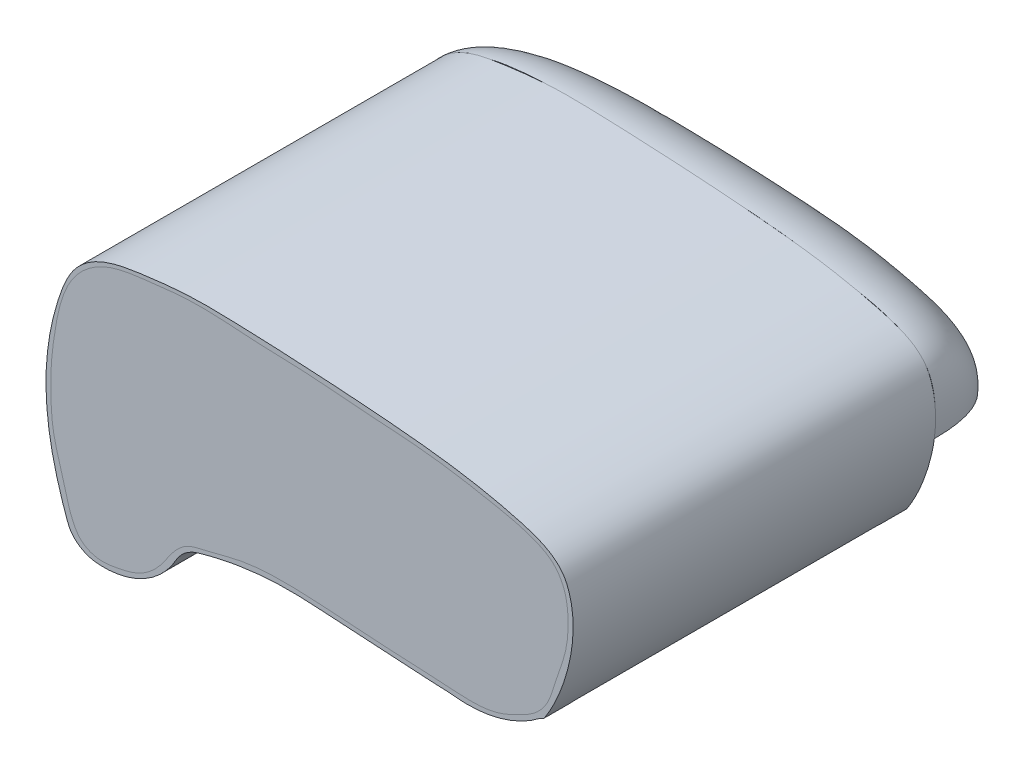
SolidWorks part; units mm, degrees
ref_plane "Front Plane" through (0, 0, 0) normal (0, 0, 1) x (1, 0, 0)
ref_plane "Top Plane" through (0, 0, 0) normal (0, 1, 0) x (1, 0, 0)
ref_plane "Right Plane" through (0, 0, 0) normal (1, 0, 0) x (0, 0, -1)
sketch "Sketch3" plane through (0, 0, 0) normal (0, 0, 1) x (1, 0, 0)
  spline S3 degree 3 poles (-30.4158, -23.6816) (-26.3483, -23.8865) (-22.7046, -22.0674) (-20.4239, -18.6933) (-20.304, -18.5158) (-20.0741, -18.1541) (-19.7633, -17.5878) (-19.5076, -17.2429) (-19.3692, -17.0794) (-18.9513, -16.5856) (-18.4465, -16.181) (-17.8735, -15.8807) (-17.7803, -15.8319) (-17.591, -15.7401) (-17.2995, -15.6137) (-17.0982, -15.5528) (-16.9975, -15.5227) (-16.8928, -15.4914) (-16.6834, -15.4297) (-16.3685, -15.3393) (-16.1582, -15.2807) (-16.0529, -15.2517) (-12.5144, -14.2781) (-8.9004, -13.7487) (-5.2109, -13.6634) (-4.334, -13.6431) (-2.579, -13.6529) (0.0505, -13.8184) (1.8017, -13.9228) (2.6773, -13.9751) (6.5229, -14.2044) (10.3686, -14.4338) (14.2143, -14.6631) (14.784, -14.6971) (15.9235, -14.7651) (17.6362, -14.8094) (18.7722, -14.935) (19.342, -14.9689) (20.3187, -15.0272) (21.2863, -14.9999) (22.7246, -14.8352) (23.2019, -14.7596) (24.152, -14.5659) (24.6269, -14.4472) (26.0289, -14.0294) (26.9249, -13.6727) (28.6409, -12.8057) (29.461, -12.2955) (30.2398, -11.7019) (30.3143, -11.6452) (30.4622, -11.5303) (30.7884, -11.4725) (30.8923, -11.3167) (30.9437, -11.2384) (31.0764, -11.0361) (31.4317, -10.4693) (31.9497, -9.5397) (32.4855, -8.4558) (32.9579, -7.3766) (33.3755, -6.2991) (33.7422, -5.2207) (34.0616, -4.1386) (34.4235, -2.6865) (34.6881, -1.2133) (34.8374, 0.2928) (34.8822, 1.442) (34.8472, 2.6121) (34.7158, 3.8044) (34.4597, 5.0136) (34.1873, 5.8271) (33.9324, 6.4006) (33.7637, 6.7398) (33.4613, 7.2204) (33.1649, 7.5894) (32.9057, 7.8653) (32.7012, 8.0623) (32.488, 8.2493) (32.2666, 8.4267) (32.0381, 8.5948) (31.8032, 8.7539) (31.5628, 8.9044) (31.2356, 9.0943) (30.8158, 9.3126) (30.2997, 9.5483) (29.7737, 9.7616) (29.2405, 9.9561) (28.5222, 10.1946) (27.6144, 10.4609) (26.5177, 10.7556) (25.416, 11.0318) (24.3094, 11.2896) (23.1984, 11.5293) (22.0832, 11.7516) (20.9645, 11.9577) (19.8424, 12.1484) (18.7174, 12.3245) (17.5896, 12.4872) (16.4595, 12.6376) (15.3272, 12.7768) (14.1929, 12.9061) (13.0567, 13.0265) (12.1085, 13.1204) (11.3492, 13.1922) (10.5893, 13.2619) (9.8286, 13.329) (9.1624, 13.3856) (8.7816, 13.4174) (8.4006, 13.4489) (7.9241, 13.4876) (7.1613, 13.5482) (6.3978, 13.6069) (5.6334, 13.6638) (5.169, 13.6977) (4.8955, 13.7173) (4.8134, 13.7232) (4.2136, 13.7661) (3.0136, 13.849) (1.2132, 13.9656) (0.0127, 14.0384) (-0.5877, 14.0736) (-0.6245, 14.0757) (-0.7575, 14.0835) (-0.9869, 14.0968) (-1.3724, 14.119) (-1.8545, 14.1462) (-2.4334, 14.1782) (-3.0128, 14.2094) (-3.5926, 14.24) (-4.1729, 14.2698) (-4.7537, 14.2989) (-5.5287, 14.3368) (-6.4986, 14.3823) (-7.6646, 14.4337) (-8.8326, 14.482) (-10.0027, 14.5267) (-11.175, 14.5674) (-12.3496, 14.6034) (-13.5265, 14.634) (-14.7059, 14.6542) (-15.8878, 14.6587) (-17.0719, 14.6418) (-18.2579, 14.5973) (-19.445, 14.5251) (-20.6326, 14.4248) (-21.8208, 14.3024) (-23.01, 14.1637) (-24.2001, 14.0094) (-25.3912, 13.8403) (-26.5814, 13.6466) (-27.7691, 13.4185) (-28.942, 13.1088) (-30.0893, 12.7041) (-31.0083, 12.2678) (-31.71, 11.8539) (-32.3847, 11.3953) (-33.1682, 10.7362) (-33.8525, 9.97) (-34.3289, 9.3004) (-34.7606, 8.5994) (-35.2215, 7.6762) (-35.534, 6.91) (-35.6795, 6.5221) (-35.9046, 5.9225) (-36.2112, 4.9903) (-36.5846, 3.6945) (-36.8438, 2.6961) (-37.0792, 1.6712) (-37.2881, 0.6207) (-37.4681, -0.4544) (-37.6656, -1.9187) (-37.8261, -3.8027) (-37.8684, -6.1288) (-37.7497, -8.4955) (-37.4776, -10.8739) (-37.0598, -13.2353) (-36.5177, -15.556) (-35.9805, -17.4362) (-35.511, -18.9018) (-35.2251, -19.7368) (-35.0582, -20.2058) (-35.0172, -20.3198) (-34.8031, -20.9157) (-34.3569, -22.1011) (-32.3076, -23.4804) (-31.0481, -23.6498) (-30.4158, -23.6816) (-26.3483, -23.8865) (-22.7046, -22.0674) knots -0.008045 0 0 0 0.061141 0.061141 0.061141 0.06466 0.068178 0.071696 0.071696 0.071696 0.082191 0.082191 0.082191 0.083918 0.085645 0.087372 0.087372 0.087372 0.089165 0.090958 0.092751 0.092751 0.092751 0.153029 0.153029 0.153029 0.167356 0.181683 0.19601 0.19601 0.19601 0.258935 0.258935 0.258935 0.268257 0.27758 0.286902 0.286902 0.286902 0.302883 0.302883 0.310873 0.310873 0.318863 0.318863 0.334844 0.334844 0.350825 0.350825 0.350825 0.352353 0.353881 0.35541 0.35541 0.35541 0.359359 0.366469 0.37358 0.380691 0.387801 0.394912 0.402023 0.409133 0.423355 0.430465 0.437576 0.444687 0.451797 0.458908 0.466019 0.466019 0.469086 0.472153 0.47522 0.476754 0.478288 0.479821 0.481355 0.482889 0.484422 0.485956 0.48749 0.490557 0.493624 0.496691 0.499759 0.502826 0.508961 0.515095 0.52123 0.527364 0.533499 0.539633 0.545768 0.551902 0.558037 0.564172 0.570306 0.576441 0.582575 0.58871 0.594844 0.597912 0.600979 0.607114 0.610181 0.611715 0.613248 0.616315 0.619383 0.625517 0.628585 0.631652 0.632969 0.632969 0.632969 0.642586 0.652203 0.66182 0.66182 0.66182 0.662408 0.663951 0.665493 0.668578 0.671663 0.674748 0.677833 0.680918 0.684003 0.687088 0.693258 0.699428 0.705598 0.711768 0.717938 0.724108 0.730278 0.736448 0.742618 0.748788 0.754958 0.761128 0.767298 0.773468 0.779638 0.785808 0.791978 0.798148 0.804318 0.810488 0.816658 0.822828 0.825913 0.828998 0.835168 0.841338 0.844423 0.847508 0.853678 0.859848 0.859848 0.859848 0.869388 0.874158 0.878928 0.883697 0.888467 0.893237 0.898007 0.907547 0.917087 0.926626 0.936166 0.945706 0.955246 0.964785 0.969555 0.974325 0.975865 0.975865 0.975865 0.98391 0.991955 1 1 1 1.061141 1.061141 1.061141 weights 1 0.914065 0.914065 1 1 1 1 1 1 0.987638 0.987638 1 1 1 1 1 1 1 1 1 1 1 1 1 1 1 1 1 1 1 1 1 1 1 1 1 1 1 1 1 1 1 1 1 1 1 1 1 1 1 1 1 1 1 1 1 1 1 1 1 1 1 1 1 1 1 1 1 1 1 1 1 1 1 1 1 1 1 1 1 1 1 1 1 1 1 1 1 1 1 1 1 1 1 1 1 1 1 1 1 1 1 1 1 1 1 1 1 1 1 1 1 1 1 1 1 1 1 1 1 1 1 1 1 1 1 1 1 1 1 1 1 1 1 1 1 1 1 1 1 1 1 1 1 1 1 1 1 1 1 1 1 1 1 1 1 1 1 1 1 1 1 1 1 1 1 1 1 1 1 1 1 1 1 1 1 1 1 1 1 1 1 1 1 1 1 0.914065 0.914065 only from (-30.4158, -23.6816) to (-30.4158, -23.6816)
extrude "Boss-Extrude2" add sketch "Sketch3" along normal blind 50 contours S3
sketch "Sketch9" plane through (0, 0, 0) normal (0, 0, -1) x (-1, 0, 0)
  spline S0 degree 3 poles (-33.7977, 5.4801) (-34.2769, 2.2354) (-34.1307, -1.2126) (-33.109, -4.2704) (-32.2134, -6.809) (-31.5466, -9.246) (-29.7466, -11.4487) (-27.1947, -12.8028) (-24.1608, -14.2194) (-20.3031, -14.453) (-16.4026, -14.0795) (-12.0077, -13.963) (-7.3255, -13.6383) (-2.5563, -13.3667) (1.662, -13.0676) (6.216, -12.9574) (10.8881, -13.2764) (15.1467, -14.5868) (18.3871, -15.1317) (20.5451, -17.2018) (22.0719, -19.8862) (24.7577, -22.1348) (27.9522, -22.8781) (30.6512, -23.2861) (33.324, -22.1675) (34.7011, -19.1807) (35.5824, -15.3471) (36.9492, -11.2903) (37.1798, -7.2911) (37.2241, -3.3615) (36.5434, 2.162) (35.2376, 8.5059) (29.7403, 12.8242) (23.7734, 13.5518) (16.5418, 14.4104) (9.2281, 13.6486) (1.7371, 13.5774) (-5.373, 12.8392) (-12.6921, 12.5283) (-19.0263, 11.6976) (-24.4576, 10.6457) (-28.6935, 9.775) (-32.2385, 8.0599) (-33.7977, 5.4801) (-34.2769, 2.2354) (-34.1307, -1.2126) knots -0.045991 -0.028791 -0.014028 0 0.0233 0.040373 0.051295 0.066461 0.080359 0.09526 0.112321 0.133474 0.155863 0.175167 0.203706 0.230933 0.251572 0.2713 0.30388 0.325554 0.343002 0.354716 0.371808 0.392562 0.408082 0.423887 0.435416 0.451508 0.473479 0.499302 0.519191 0.537282 0.561981 0.608952 0.634675 0.667939 0.703139 0.751398 0.784732 0.822979 0.865597 0.901841 0.925029 0.954009 0.971209 0.985972 1 1.0233 1.040373 1.051295 only from (-34.1289, 2.8072) to (-34.1289, 2.8072)
extrude "Cut-Extrude4" cut sketch "Sketch9" against normal blind 50
sketch "Sketch17" plane through (0, 0, 0) normal (0, 0, -1) x (-1, 0, 0)
  line L0 (-34.6868, -1.0559) -> (35.6264, 6.6621)
  spline S0 degree 3 poles (30.4158, -23.6816) (31.0481, -23.6498) (32.3076, -23.4804) (34.3569, -22.1011) (34.8031, -20.9157) (35.0172, -20.3198) (35.0582, -20.2058) (35.2251, -19.7368) (35.511, -18.9018) (35.9805, -17.4362) (36.5177, -15.556) (37.0598, -13.2353) (37.4776, -10.8739) (37.7497, -8.4955) (37.8684, -6.1288) (37.8261, -3.8027) (37.6656, -1.9187) (37.4681, -0.4544) (37.2881, 0.6207) (37.0792, 1.6712) (36.8438, 2.6961) (36.5846, 3.6945) (36.2112, 4.9903) (35.9046, 5.9225) (35.6795, 6.5221) (35.534, 6.91) (35.2215, 7.6762) (34.7606, 8.5994) (34.3289, 9.3004) (33.8525, 9.97) (33.1682, 10.7362) (32.3847, 11.3953) (31.71, 11.8539) (31.0083, 12.2678) (30.0893, 12.7041) (28.942, 13.1088) (27.7691, 13.4185) (26.5814, 13.6466) (25.3912, 13.8403) (24.2001, 14.0094) (23.01, 14.1637) (21.8208, 14.3024) (20.6326, 14.4248) (19.445, 14.5251) (18.2579, 14.5973) (17.0719, 14.6418) (15.8878, 14.6587) (14.7059, 14.6542) (13.5265, 14.634) (12.3496, 14.6034) (11.175, 14.5674) (10.0027, 14.5267) (8.8326, 14.482) (7.6646, 14.4337) (6.4986, 14.3823) (5.5287, 14.3368) (4.7537, 14.2989) (4.1729, 14.2698) (3.5926, 14.24) (3.0128, 14.2094) (2.4334, 14.1782) (1.8545, 14.1462) (1.3724, 14.119) (0.9869, 14.0968) (0.7575, 14.0835) (0.6245, 14.0757) (0.5877, 14.0736) (-0.0127, 14.0384) (-1.2132, 13.9656) (-3.0136, 13.849) (-4.2136, 13.7661) (-4.8134, 13.7232) (-4.8955, 13.7173) (-5.169, 13.6977) (-5.6334, 13.6638) (-6.3978, 13.6069) (-7.1613, 13.5482) (-7.9241, 13.4876) (-8.4006, 13.4489) (-8.7816, 13.4174) (-9.1624, 13.3856) (-9.8286, 13.329) (-10.5893, 13.2619) (-11.3492, 13.1922) (-12.1085, 13.1204) (-13.0567, 13.0265) (-14.1929, 12.9061) (-15.3272, 12.7768) (-16.4595, 12.6376) (-17.5896, 12.4872) (-18.7174, 12.3245) (-19.8424, 12.1484) (-20.9645, 11.9577) (-22.0832, 11.7516) (-23.1984, 11.5293) (-24.3094, 11.2896) (-25.416, 11.0318) (-26.5177, 10.7556) (-27.6144, 10.4609) (-28.5222, 10.1946) (-29.2405, 9.9561) (-29.7737, 9.7616) (-30.2997, 9.5483) (-30.8158, 9.3126) (-31.2356, 9.0943) (-31.5628, 8.9044) (-31.8032, 8.7539) (-32.0381, 8.5948) (-32.2666, 8.4267) (-32.488, 8.2493) (-32.7012, 8.0623) (-32.9057, 7.8653) (-33.1649, 7.5894) (-33.4613, 7.2204) (-33.7637, 6.7398) (-33.9324, 6.4006) (-34.1873, 5.8271) (-34.4597, 5.0136) (-34.7158, 3.8044) (-34.8472, 2.6121) (-34.8822, 1.442) (-34.8374, 0.2928) (-34.6881, -1.2133) (-34.4235, -2.6865) (-34.0616, -4.1386) (-33.7422, -5.2207) (-33.3755, -6.2991) (-32.9579, -7.3766) (-32.4855, -8.4558) (-31.9497, -9.5397) (-31.4317, -10.4693) (-31.0764, -11.0361) (-30.9437, -11.2384) (-30.8923, -11.3167) (-30.7884, -11.4725) (-30.4622, -11.5303) (-30.3143, -11.6452) (-30.2398, -11.7019) (-29.461, -12.2955) (-28.6409, -12.8057) (-26.9249, -13.6727) (-26.0289, -14.0294) (-24.6269, -14.4472) (-24.152, -14.5659) (-23.2019, -14.7596) (-22.7246, -14.8352) (-21.2863, -14.9999) (-20.3187, -15.0272) (-19.342, -14.9689) (-18.7722, -14.935) (-17.6362, -14.8094) (-15.9235, -14.7651) (-14.784, -14.6971) (-14.2143, -14.6631) (-10.3686, -14.4338) (-6.5229, -14.2044) (-2.6773, -13.9751) (-1.8017, -13.9228) (-0.0505, -13.8184) (2.579, -13.6529) (4.334, -13.6431) (5.2109, -13.6634) (8.9004, -13.7487) (12.5144, -14.2781) (16.0529, -15.2517) (16.1582, -15.2807) (16.3685, -15.3393) (16.6834, -15.4297) (16.8928, -15.4914) (16.9975, -15.5227) (17.0982, -15.5528) (17.2995, -15.6137) (17.591, -15.7401) (17.7803, -15.8319) (17.8735, -15.8807) (18.4465, -16.181) (18.9513, -16.5856) (19.3692, -17.0794) (19.5076, -17.2429) (19.7633, -17.5878) (20.0741, -18.1541) (20.304, -18.5158) (20.4239, -18.6933) (22.7046, -22.0674) (26.3483, -23.8865) (30.4158, -23.6816) (31.0481, -23.6498) (32.3076, -23.4804) knots -0.061141 0 0 0 0.008045 0.01609 0.024135 0.024135 0.024135 0.025675 0.030445 0.035215 0.044754 0.054294 0.063834 0.073374 0.082913 0.092453 0.101993 0.106763 0.111533 0.116303 0.121072 0.125842 0.130612 0.140152 0.140152 0.140152 0.146322 0.152492 0.155577 0.158662 0.164832 0.171002 0.174087 0.177172 0.183342 0.189512 0.195682 0.201852 0.208022 0.214192 0.220362 0.226532 0.232702 0.238872 0.245042 0.251212 0.257382 0.263552 0.269722 0.275892 0.282062 0.288232 0.294402 0.300572 0.306742 0.312912 0.315997 0.319082 0.322167 0.325252 0.328337 0.331422 0.334507 0.336049 0.337592 0.33818 0.33818 0.33818 0.347797 0.357414 0.367031 0.367031 0.367031 0.368348 0.371415 0.374483 0.380617 0.383685 0.386752 0.388285 0.389819 0.392886 0.399021 0.402088 0.405156 0.41129 0.417425 0.423559 0.429694 0.435828 0.441963 0.448098 0.454232 0.460367 0.466501 0.472636 0.47877 0.484905 0.491039 0.497174 0.500241 0.503309 0.506376 0.509443 0.51251 0.514044 0.515578 0.517111 0.518645 0.520179 0.521712 0.523246 0.52478 0.527847 0.530914 0.533981 0.533981 0.541092 0.548203 0.555313 0.562424 0.569535 0.576645 0.590867 0.597977 0.605088 0.612199 0.619309 0.62642 0.633531 0.640641 0.64459 0.64459 0.64459 0.646119 0.647647 0.649175 0.649175 0.649175 0.665156 0.665156 0.681137 0.681137 0.689127 0.689127 0.697117 0.697117 0.713098 0.713098 0.713098 0.72242 0.731743 0.741065 0.741065 0.741065 0.80399 0.80399 0.80399 0.818317 0.832644 0.846971 0.846971 0.846971 0.907249 0.907249 0.907249 0.909042 0.910835 0.912628 0.912628 0.912628 0.914355 0.916082 0.917809 0.917809 0.917809 0.928304 0.928304 0.928304 0.931822 0.93534 0.938859 0.938859 0.938859 1 1 1 1.008045 1.01609 1.024135 weights 1 1 1 1 1 1 1 1 1 1 1 1 1 1 1 1 1 1 1 1 1 1 1 1 1 1 1 1 1 1 1 1 1 1 1 1 1 1 1 1 1 1 1 1 1 1 1 1 1 1 1 1 1 1 1 1 1 1 1 1 1 1 1 1 1 1 1 1 1 1 1 1 1 1 1 1 1 1 1 1 1 1 1 1 1 1 1 1 1 1 1 1 1 1 1 1 1 1 1 1 1 1 1 1 1 1 1 1 1 1 1 1 1 1 1 1 1 1 1 1 1 1 1 1 1 1 1 1 1 1 1 1 1 1 1 1 1 1 1 1 1 1 1 1 1 1 1 1 1 1 1 1 1 1 1 1 1 1 1 1 1 1 1 1 1 1 1 1 1 1 1 1 1 1 1 0.987638 0.987638 1 1 1 1 1 1 0.914065 0.914065 1 1 1 only from (30.4158, -23.6816) to (30.4158, -23.6816) construction
  spline S1 degree 3 poles (-34.6868, -1.0559) (-34.9459, 1.4826) (-35.1783, 6.9566) (-29.3346, 10.198) (-23.6766, 11.4658) (-16.1466, 12.8119) (-7.7529, 13.5278) (0.621, 14.0984) (9.4185, 14.5408) (18.0794, 14.7646) (28.0773, 13.8367) (34.5801, 10.9823) (35.6264, 6.6621) knots 0 0 0 0 0.105545 0.158729 0.2294 0.320597 0.438441 0.53874 0.628645 0.762133 0.855322 1 1 1 1
revolve "Revolve1" add sketch "Sketch17" angle 90 about L0
sketch "Sketch18" plane through (0, 0, 0) normal (0, 0, 1) x (1, 0, 0)
  spline S3 degree 3 poles (-30.4158, -23.6816) (-26.3483, -23.8865) (-22.7046, -22.0674) (-20.4239, -18.6933) (-20.304, -18.5158) (-20.0741, -18.1541) (-19.7633, -17.5878) (-19.5076, -17.2429) (-19.3692, -17.0794) (-18.9513, -16.5856) (-18.4465, -16.181) (-17.8735, -15.8807) (-17.7803, -15.8319) (-17.591, -15.7401) (-17.2995, -15.6137) (-17.0982, -15.5528) (-16.9975, -15.5227) (-16.8928, -15.4914) (-16.6834, -15.4297) (-16.3685, -15.3393) (-16.1582, -15.2807) (-16.0529, -15.2517) (-12.5144, -14.2781) (-8.9004, -13.7487) (-5.2109, -13.6634) (-4.334, -13.6431) (-2.579, -13.6529) (0.0505, -13.8184) (1.8017, -13.9228) (2.6773, -13.9751) (6.5229, -14.2044) (10.3686, -14.4338) (14.2143, -14.6631) (14.784, -14.6971) (15.9235, -14.7651) (17.6362, -14.8094) (18.7722, -14.935) (19.342, -14.9689) (20.3187, -15.0272) (21.2863, -14.9999) (22.7246, -14.8352) (23.2019, -14.7596) (24.152, -14.5659) (24.6269, -14.4472) (26.0289, -14.0294) (26.9249, -13.6727) (28.6409, -12.8057) (29.461, -12.2955) (30.2398, -11.7019) (30.3143, -11.6452) (30.4622, -11.5303) (30.7884, -11.4725) (30.8923, -11.3167) (30.9437, -11.2384) (31.0764, -11.0361) (31.4317, -10.4693) (31.9497, -9.5397) (32.4855, -8.4558) (32.9579, -7.3766) (33.3755, -6.2991) (33.7422, -5.2207) (34.0616, -4.1386) (34.4235, -2.6865) (34.6881, -1.2133) (34.8374, 0.2928) (34.8822, 1.442) (34.8472, 2.6121) (34.7158, 3.8044) (34.4597, 5.0136) (34.1873, 5.8271) (33.9324, 6.4006) (33.7637, 6.7398) (33.4613, 7.2204) (33.1649, 7.5894) (32.9057, 7.8653) (32.7012, 8.0623) (32.488, 8.2493) (32.2666, 8.4267) (32.0381, 8.5948) (31.8032, 8.7539) (31.5628, 8.9044) (31.2356, 9.0943) (30.8158, 9.3126) (30.2997, 9.5483) (29.7737, 9.7616) (29.2405, 9.9561) (28.5222, 10.1946) (27.6144, 10.4609) (26.5177, 10.7556) (25.416, 11.0318) (24.3094, 11.2896) (23.1984, 11.5293) (22.0832, 11.7516) (20.9645, 11.9577) (19.8424, 12.1484) (18.7174, 12.3245) (17.5896, 12.4872) (16.4595, 12.6376) (15.3272, 12.7768) (14.1929, 12.9061) (13.0567, 13.0265) (12.1085, 13.1204) (11.3492, 13.1922) (10.5893, 13.2619) (9.8286, 13.329) (9.1624, 13.3856) (8.7816, 13.4174) (8.4006, 13.4489) (7.9241, 13.4876) (7.1613, 13.5482) (6.3978, 13.6069) (5.6334, 13.6638) (5.169, 13.6977) (4.8955, 13.7173) (4.8134, 13.7232) (4.2136, 13.7661) (3.0136, 13.849) (1.2132, 13.9656) (0.0127, 14.0384) (-0.5877, 14.0736) (-0.6245, 14.0757) (-0.7575, 14.0835) (-0.9869, 14.0968) (-1.3724, 14.119) (-1.8545, 14.1462) (-2.4334, 14.1782) (-3.0128, 14.2094) (-3.5926, 14.24) (-4.1729, 14.2698) (-4.7537, 14.2989) (-5.5287, 14.3368) (-6.4986, 14.3823) (-7.6646, 14.4337) (-8.8326, 14.482) (-10.0027, 14.5267) (-11.175, 14.5674) (-12.3496, 14.6034) (-13.5265, 14.634) (-14.7059, 14.6542) (-15.8878, 14.6587) (-17.0719, 14.6418) (-18.2579, 14.5973) (-19.445, 14.5251) (-20.6326, 14.4248) (-21.8208, 14.3024) (-23.01, 14.1637) (-24.2001, 14.0094) (-25.3912, 13.8403) (-26.5814, 13.6466) (-27.7691, 13.4185) (-28.942, 13.1088) (-30.0893, 12.7041) (-31.0083, 12.2678) (-31.71, 11.8539) (-32.3847, 11.3953) (-33.1682, 10.7362) (-33.8525, 9.97) (-34.3289, 9.3004) (-34.7606, 8.5994) (-35.2215, 7.6762) (-35.534, 6.91) (-35.6795, 6.5221) (-35.9046, 5.9225) (-36.2112, 4.9903) (-36.5846, 3.6945) (-36.8438, 2.6961) (-37.0792, 1.6712) (-37.2881, 0.6207) (-37.4681, -0.4544) (-37.6656, -1.9187) (-37.8261, -3.8027) (-37.8684, -6.1288) (-37.7497, -8.4955) (-37.4776, -10.8739) (-37.0598, -13.2353) (-36.5177, -15.556) (-35.9805, -17.4362) (-35.511, -18.9018) (-35.2251, -19.7368) (-35.0582, -20.2058) (-35.0172, -20.3198) (-34.8031, -20.9157) (-34.3569, -22.1011) (-32.3076, -23.4804) (-31.0481, -23.6498) (-30.4158, -23.6816) (-26.3483, -23.8865) (-22.7046, -22.0674) knots -0.008045 0 0 0 0.061141 0.061141 0.061141 0.06466 0.068178 0.071696 0.071696 0.071696 0.082191 0.082191 0.082191 0.083918 0.085645 0.087372 0.087372 0.087372 0.089165 0.090958 0.092751 0.092751 0.092751 0.153029 0.153029 0.153029 0.167356 0.181683 0.19601 0.19601 0.19601 0.258935 0.258935 0.258935 0.268257 0.27758 0.286902 0.286902 0.286902 0.302883 0.302883 0.310873 0.310873 0.318863 0.318863 0.334844 0.334844 0.350825 0.350825 0.350825 0.352353 0.353881 0.35541 0.35541 0.35541 0.359359 0.366469 0.37358 0.380691 0.387801 0.394912 0.402023 0.409133 0.423355 0.430465 0.437576 0.444687 0.451797 0.458908 0.466019 0.466019 0.469086 0.472153 0.47522 0.476754 0.478288 0.479821 0.481355 0.482889 0.484422 0.485956 0.48749 0.490557 0.493624 0.496691 0.499759 0.502826 0.508961 0.515095 0.52123 0.527364 0.533499 0.539633 0.545768 0.551902 0.558037 0.564172 0.570306 0.576441 0.582575 0.58871 0.594844 0.597912 0.600979 0.607114 0.610181 0.611715 0.613248 0.616315 0.619383 0.625517 0.628585 0.631652 0.632969 0.632969 0.632969 0.642586 0.652203 0.66182 0.66182 0.66182 0.662408 0.663951 0.665493 0.668578 0.671663 0.674748 0.677833 0.680918 0.684003 0.687088 0.693258 0.699428 0.705598 0.711768 0.717938 0.724108 0.730278 0.736448 0.742618 0.748788 0.754958 0.761128 0.767298 0.773468 0.779638 0.785808 0.791978 0.798148 0.804318 0.810488 0.816658 0.822828 0.825913 0.828998 0.835168 0.841338 0.844423 0.847508 0.853678 0.859848 0.859848 0.859848 0.869388 0.874158 0.878928 0.883697 0.888467 0.893237 0.898007 0.907547 0.917087 0.926626 0.936166 0.945706 0.955246 0.964785 0.969555 0.974325 0.975865 0.975865 0.975865 0.98391 0.991955 1 1 1 1.061141 1.061141 1.061141 weights 1 0.914065 0.914065 1 1 1 1 1 1 0.987638 0.987638 1 1 1 1 1 1 1 1 1 1 1 1 1 1 1 1 1 1 1 1 1 1 1 1 1 1 1 1 1 1 1 1 1 1 1 1 1 1 1 1 1 1 1 1 1 1 1 1 1 1 1 1 1 1 1 1 1 1 1 1 1 1 1 1 1 1 1 1 1 1 1 1 1 1 1 1 1 1 1 1 1 1 1 1 1 1 1 1 1 1 1 1 1 1 1 1 1 1 1 1 1 1 1 1 1 1 1 1 1 1 1 1 1 1 1 1 1 1 1 1 1 1 1 1 1 1 1 1 1 1 1 1 1 1 1 1 1 1 1 1 1 1 1 1 1 1 1 1 1 1 1 1 1 1 1 1 1 1 1 1 1 1 1 1 1 1 1 1 1 1 1 1 1 1 1 0.914065 0.914065 only from (-30.4158, -23.6816) to (-30.4158, -23.6816)
surface "Surface-Fill1"
